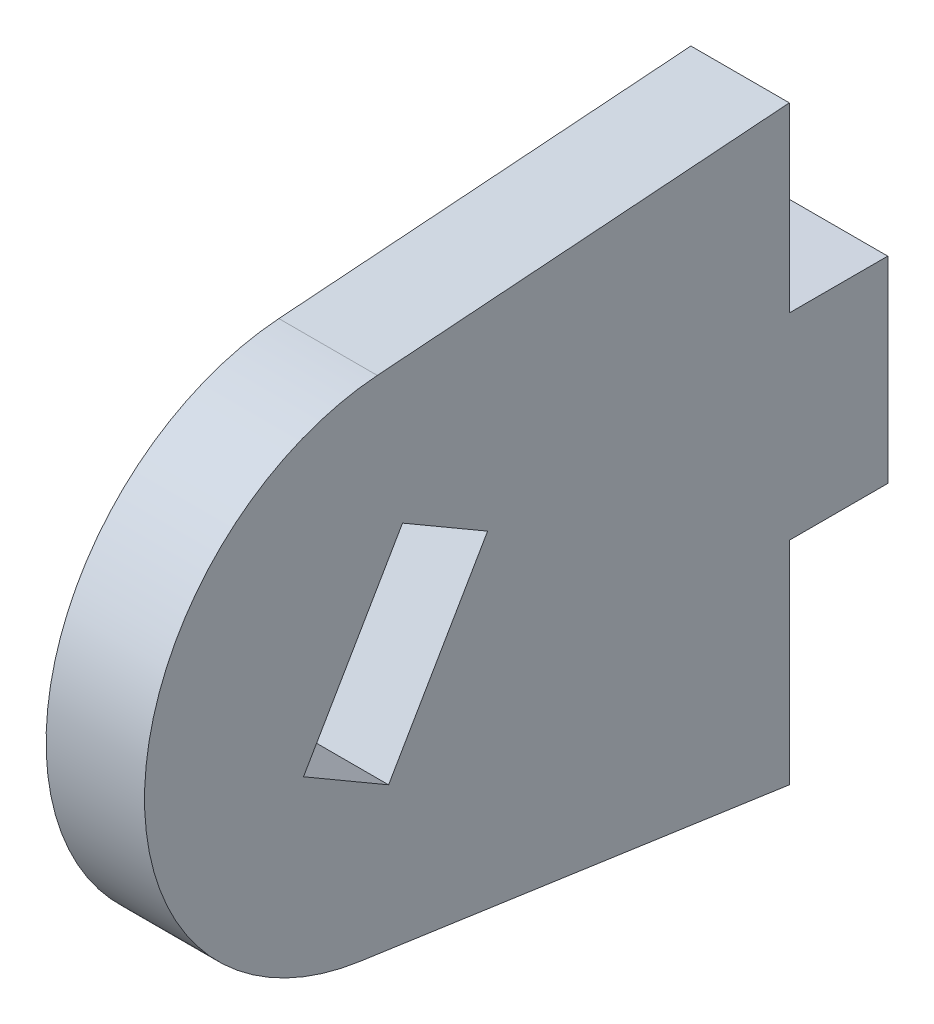
SolidWorks part; units mm, degrees
material "AISI 1020 Steel, Cold Rolled"
ref_plane "Front Plane" through (0, 0, 0) normal (1, 0, 0) x (0, 1, 0)
ref_plane "Top Plane" through (0, 0, 0) normal (0, 0, 1) x (0, 1, 0)
ref_plane "Right Plane" through (0, 0, 0) normal (0, 1, 0) x (-1, 0, 0)
sketch "Sketch1" plane through (0, 0, 0) normal (1, 0, 0) x (0, 1, 0)
  line L0 (-15.7577, 0) -> (-5, 0)
  line L1 (0, 0) -> (0, 20) construction
  line L2 (-15.7577, 0) -> (-12.6201, 21.8151)
  line L3 (14.2423, 0) -> (12.7162, 20.9273)
  line L4 (0, 0) -> (0, -5) construction
  line L5 (5, -5) -> (-5, -5)
  line L6 (-5, -5) -> (-5, 0)
  line L7 (5, -5) -> (5, 0)
  line L8 (5, 0) -> (14.2423, 0)
  line L9 (0, 0) -> (5, 0) construction
  line L10 (-5, 0) -> (0, 0) construction
  line L11 (0, 20) -> (0, 4.6155) construction
  line L12 (0, 20) -> (1.2574, 22.1608) construction
  line L13 (0, 20) -> (9.5831, 20) construction
  line L14 (5.5789, 19.646) -> (-3.0642, 24.6756)
  line L15 (-3.0642, 24.6756) -> (-5.5789, 20.354)
  line L16 (-5.5789, 20.354) -> (3.0642, 15.3244)
  line L17 (3.0642, 15.3244) -> (5.5789, 19.646)
  arc A1 (12.7162, 20.9273) -> (-12.6201, 21.8151) centre (0, 20) ccw
  arc A2 (0, 7.25) -> (12.7162, 20.9273) centre (0, 20) ccw construction
  point P4 (0, 0)
  point P11 (12, 20)
  point P17 (0, -5)
  point P23 (1.2574, 22.1608)
  dimension "D3" = 10
  dimension "D4" = 2.5
  dimension "D1" = 30
  dimension "D2" = 20
  dimension "D5" = 5
  dimension "D6" = 10
  dimension "D7" = 15.3845
  dimension "5" = 5
extrude "Boss-Extrude1" add sketch "Sketch1" along normal mid plane 5
